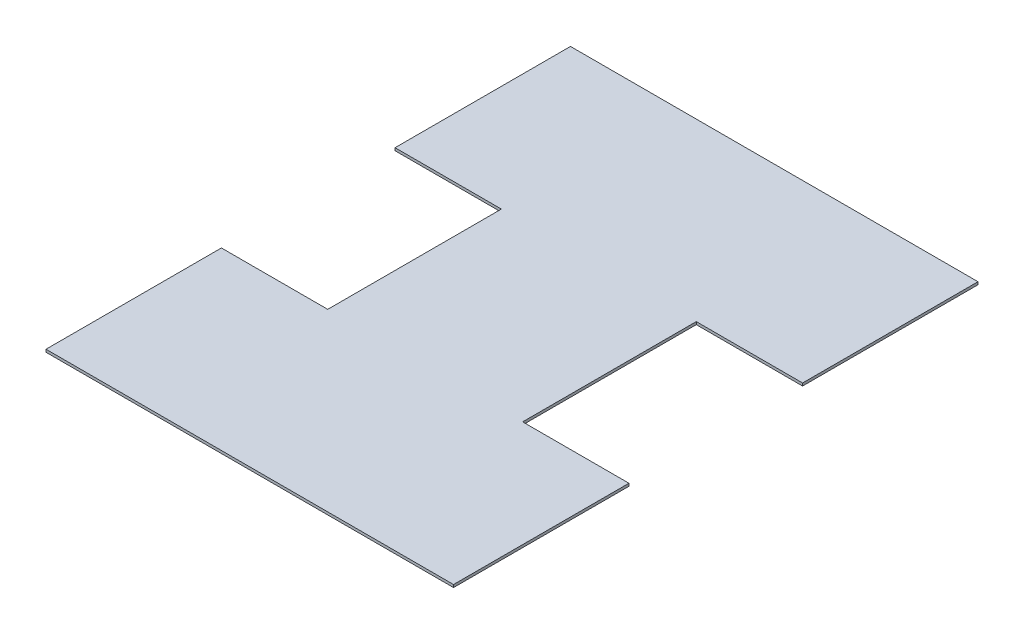
SolidWorks part; units mm, degrees
ref_plane "Front Plane" through (0, 0, 0) normal (0, 0, 1) x (1, 0, 0)
ref_plane "Top Plane" through (0, 0, 0) normal (0, 1, 0) x (1, 0, 0)
ref_plane "Right Plane" through (0, 0, 0) normal (1, 0, 0) x (0, 0, -1)
sketch "Sketch1" plane through (0, 0, 0) normal (0, 1, 0) x (1, 0, 0)
  line L0 (0, 296) -> (0, -296) construction
  line L1 (-230, -296) -> (230, -296)
  line L2 (-230, -296) -> (-230, -98)
  line L3 (-230, 296) -> (230, 296)
  line L4 (230, -296) -> (230, -98)
  line L5 (-230, -296) -> (230, 296) construction
  line L6 (-230, 296) -> (230, -296) construction
  line L7 (-230, 0) -> (230, 0) construction
  line L8 (-230, -98) -> (-110, -98)
  line L9 (-110, -98) -> (-110, 98)
  line L10 (-230, 98) -> (-110, 98)
  line L11 (230, -98) -> (110, -98)
  line L12 (110, -98) -> (110, 98)
  line L13 (230, 98) -> (110, 98)
  line L14 (230, 98) -> (230, 296)
  line L15 (-230, 98) -> (-230, 296)
  line L16 (230, 98) -> (230, -98) construction
  line L17 (-230, 98) -> (-230, -98) construction
  point P0 (0, 0)
  point P21 (-110, 0)
  dimension "D1" = 460
  dimension "D2" = 592
  dimension "D3" = 98
  dimension "D4" = 120
extrude "Boss-Extrude1" add sketch "Sketch1" along normal blind 3
